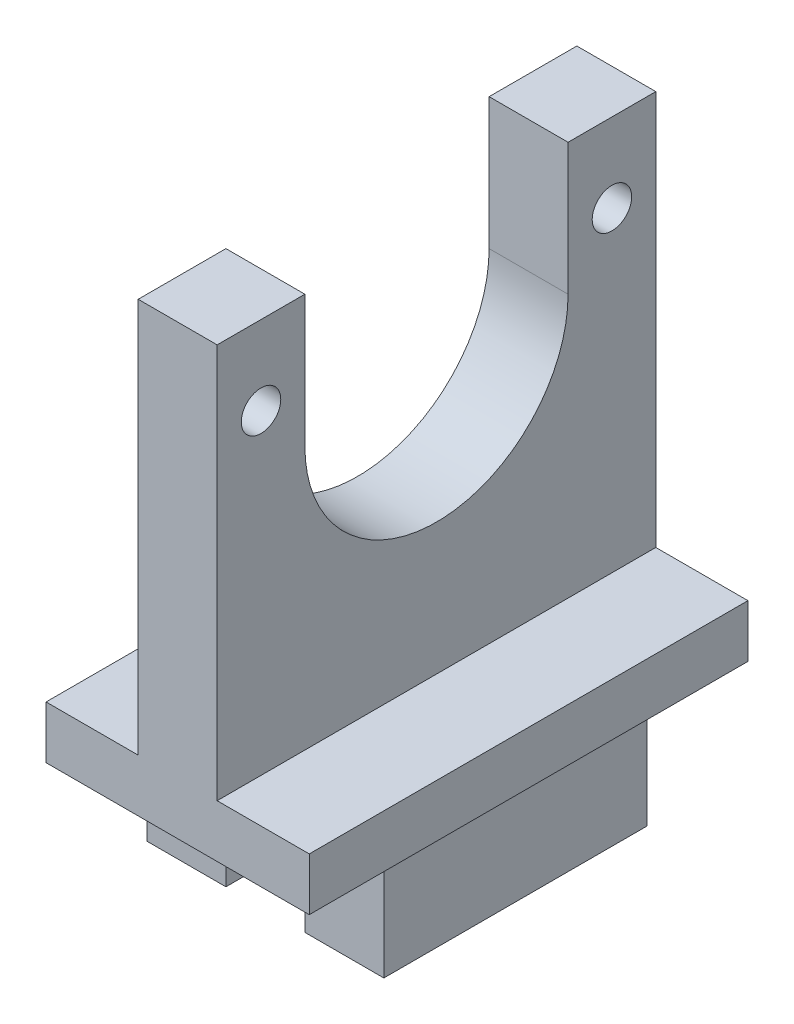
SolidWorks part; units mm, degrees
ref_plane "Front Plane" through (0, 0, 0) normal (0, 0, 1) x (1, 0, 0)
ref_plane "Top Plane" through (0, 0, 0) normal (0, 1, 0) x (1, 0, 0)
ref_plane "Right Plane" through (0, 0, 0) normal (1, 0, 0) x (0, 0, -1)
sketch "Sketch1" plane through (0, 0, 0) normal (0, 0, 1) x (1, 0, 0)
  line L0 (-1.5, -2) -> (-1.5, 0)
  line L1 (4.5, 2) -> (-4.5, 2)
  line L2 (4.5, 2) -> (4.5, -2)
  line L3 (4.5, -2) -> (1.5, -2)
  line L4 (-4.5, 2) -> (-4.5, -2)
  line L5 (4.5, 2) -> (-4.5, -2) construction
  line L6 (4.5, -2) -> (-4.5, 2) construction
  line L7 (-1.5, 0) -> (1.5, 0)
  line L8 (1.5, 0) -> (1.5, -2)
  line L9 (-1.5, -2) -> (-4.5, -2)
  point P0 (0, 0)
  point P9 (0, 0)
  dimension "D1" = 3
  dimension "D2" = 2
  dimension "D3" = 3
extrude "Boss-Extrude1" add sketch "Sketch1" along normal blind 10
sketch "Sketch2" plane through (0, 2, 0) normal (0, 1, 0) x (1, 0, 0)
  line L0 (-4.5, 0) -> (4.5, -10) construction
  line L1 (4.5, -10) -> (4.5, 0) construction
  line L2 (4.5, 0) -> (-4.5, -10) construction
  line L4 (5, 3.3333) -> (-5, 3.3333)
  line L5 (5, 3.3333) -> (5, -13.3333)
  line L6 (5, -13.3333) -> (-5, -13.3333)
  line L7 (-5, 3.3333) -> (-5, -13.3333)
  line L8 (5, 3.3333) -> (-5, -13.3333) construction
  line L9 (5, -13.3333) -> (-5, 3.3333) construction
  point P8 (0, -5)
  dimension "D1" = 10
extrude "Boss-Extrude2" add sketch "Sketch2" along normal blind 2
sketch "Sketch3" plane through (0, 0, 13.3333) normal (0, 0, 1) x (1, 0, 0)
  line L0 (-5, 4) -> (5, 4) construction
  line L1 (1.5, 4) -> (-1.5, 4)
  line L2 (1.5, 4) -> (1.5, 19)
  line L3 (1.5, 19) -> (-1.5, 19)
  line L4 (-1.5, 4) -> (-1.5, 19)
  line L5 (1.5, 4) -> (-1.5, 19) construction
  line L6 (1.5, 19) -> (-1.5, 4) construction
  line L7 (-1.5, 0) -> (-1.5, 4) construction
  line L8 (1.5, 0) -> (1.5, 4) construction
  point P4 (0, 11.5)
  dimension "D1" = 15
extrude "Boss-Extrude3" add sketch "Sketch3" against normal up to surface (16.6667 mm away) up to face at (0, 3, -3.3333)
sketch "Sketch4" plane through (-1.5, 0, 0) normal (-1, 0, 0) x (0, 0, 1)
  line L1 (-3.3333, 19) -> (13.3333, 19) construction
  line L2 (0, 14) -> (0, 19)
  line L3 (10, 14) -> (10, 19)
  line L4 (10, 19) -> (0, 19)
  arc A0 (0, 14) -> (10, 14) centre (5, 14) ccw
  dimension "D2" = 10
extrude "Cut-Extrude1" cut sketch "Sketch4" against normal through all
sketch "Sketch5" plane through (-1.5, 0, 0) normal (-1, 0, 0) x (0, 0, 1)
  line L0 (-1.6667, 16) -> (11.6667, 16) construction
  line L1 (11.6667, 16) -> (11.6667, 19) construction
  line L2 (10, 19) -> (13.3333, 19) construction
  line L3 (11.6667, 19) -> (-1.6667, 19) construction
  line L4 (-3.3333, 19) -> (0, 19) construction
  line L5 (-1.6667, 19) -> (-1.6667, 16) construction
  circle A0 centre (11.6667, 16) radius 0.75
  circle A1 centre (-1.6667, 16) radius 0.75
  dimension "D1" = 1.5
  dimension "D2" = 1.5
  dimension "D3" = 3
extrude "Cut-Extrude2" cut sketch "Sketch5" against normal through all
